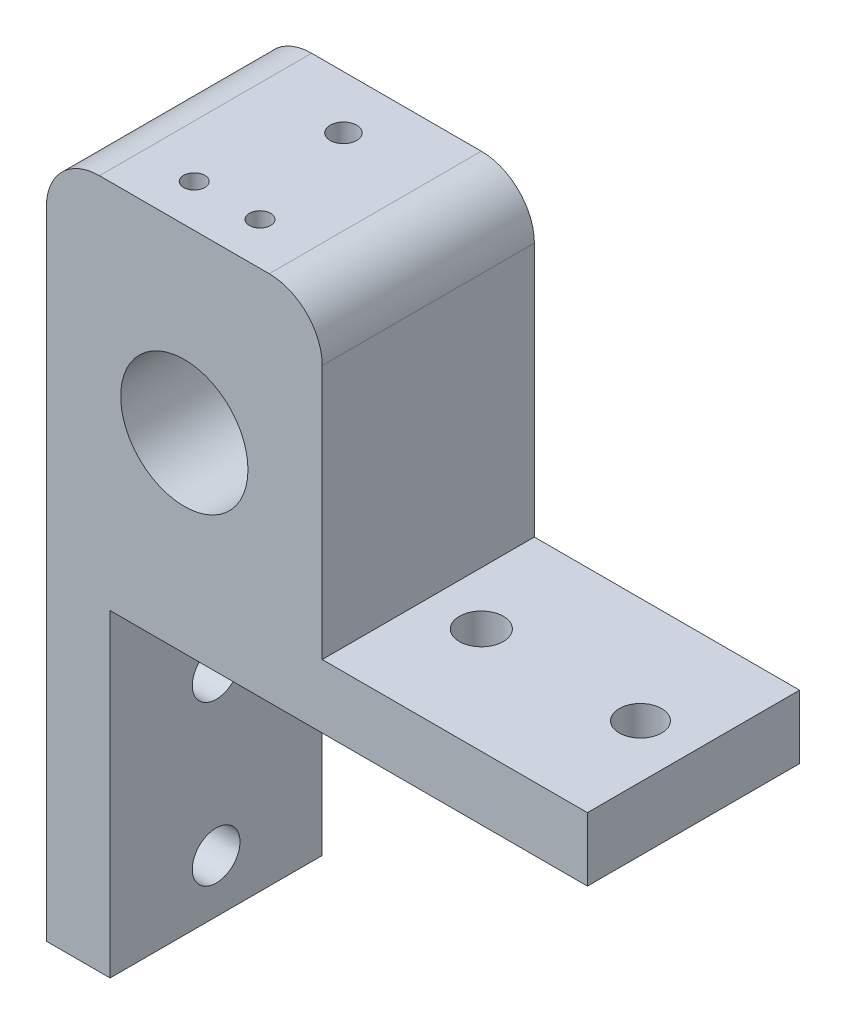
SolidWorks part; units mm, degrees
ref_plane "Front Plane" through (0, 0, 0) normal (0, 0, 1) x (1, 0, 0)
ref_plane "Top Plane" through (0, 0, 0) normal (0, 1, 0) x (1, 0, 0)
ref_plane "Right Plane" through (0, 0, 0) normal (1, 0, 0) x (0, 0, -1)
sketch "Sketch1" plane through (0, 0, 0) normal (0, 0, 1) x (1, 0, 0)
  line L1 (-13, 22) -> (13, 22)
  line L2 (-13, 22) -> (-13, -4)
  line L3 (-7, -13) -> (13, -13)
  line L4 (13, 22) -> (13, -7)
  line L5 (-13, 22) -> (13, -13) construction
  line L6 (-13, -4) -> (13, 22) construction
  line L8 (-13, -4) -> (-13, -43)
  line L9 (-13, -43) -> (-7, -43)
  line L10 (-7, -13) -> (-7, -43)
  line L11 (13, -13) -> (38, -13)
  line L13 (13, -7) -> (38, -7)
  line L14 (38, -13) -> (38, -7)
  circle A0 centre (0, 5) radius 6
  dimension "D1" = 12
  dimension "D2" = 35
  dimension "D3" = 26
  dimension "D4" = 30
  dimension "D5" = 6
  dimension "D6" = 6
  dimension "D7" = 25
  dimension "D8" = 18
extrude "Boss-Extrude1" add sketch "Sketch1" along normal blind 20
sketch "Sketch2" plane through (-13, 0, 0) normal (-1, 0, 0) x (0, 0, 1)
  line L0 (20, -43) -> (0, -43) construction
  circle A0 centre (10, -38) radius 2.25
  circle A1 centre (10, -23) radius 2.25
  dimension "D2" = 4.5
  dimension "D3" = 4.5
  dimension "D1" = 5
  dimension "D4" = 20
extrude "Cut-Extrude1" cut sketch "Sketch2" against normal blind 20
sketch "Sketch3" plane through (0, -7, 0) normal (0, 1, 0) x (1, 0, 0)
  line L0 (38, -20) -> (38, 0) construction
  line L1 (38, 0) -> (13, 0) construction
  circle A0 centre (33, -10) radius 2
  circle A1 centre (18, -10) radius 2.0704
  dimension "D1" = 4
  dimension "D3" = 10
  dimension "D2" = 5
  dimension "D4" = 15
extrude "Cut-Extrude2" cut sketch "Sketch3" against normal blind 20
fillet "Fillet1" radius 5 2 edges at (-13, 22, 10) (13, 22, 10)
sketch "Sketch4" plane through (0, 0, 20) normal (0, 0, 1) x (1, 0, 0)
  line L0 (0, 22) -> (0, 21.1407)
  line L1 (8, 22) -> (-8, 22) construction
sketch "Sketch5" plane through (0, 22, 0) normal (0, 1, 0) x (1, 0, 0)
  line L0 (8, 0) -> (-8, 0) construction
  circle A0 centre (0, -5) radius 1.25
  dimension "D1" = 2.5
  dimension "D2" = 5
extrude "Cut-Extrude3" cut sketch "Sketch5" against normal up to next
sketch "Sketch6" plane through (0, 22, 0) normal (0, 1, 0) x (1, 0, 0)
  circle A0 centre (3.1322, -16) radius 1
  circle A1 centre (-3.0678, -16) radius 1
  dimension "D1" = 2
extrude "Cut-Extrude4" cut sketch "Sketch6" against normal blind 10
